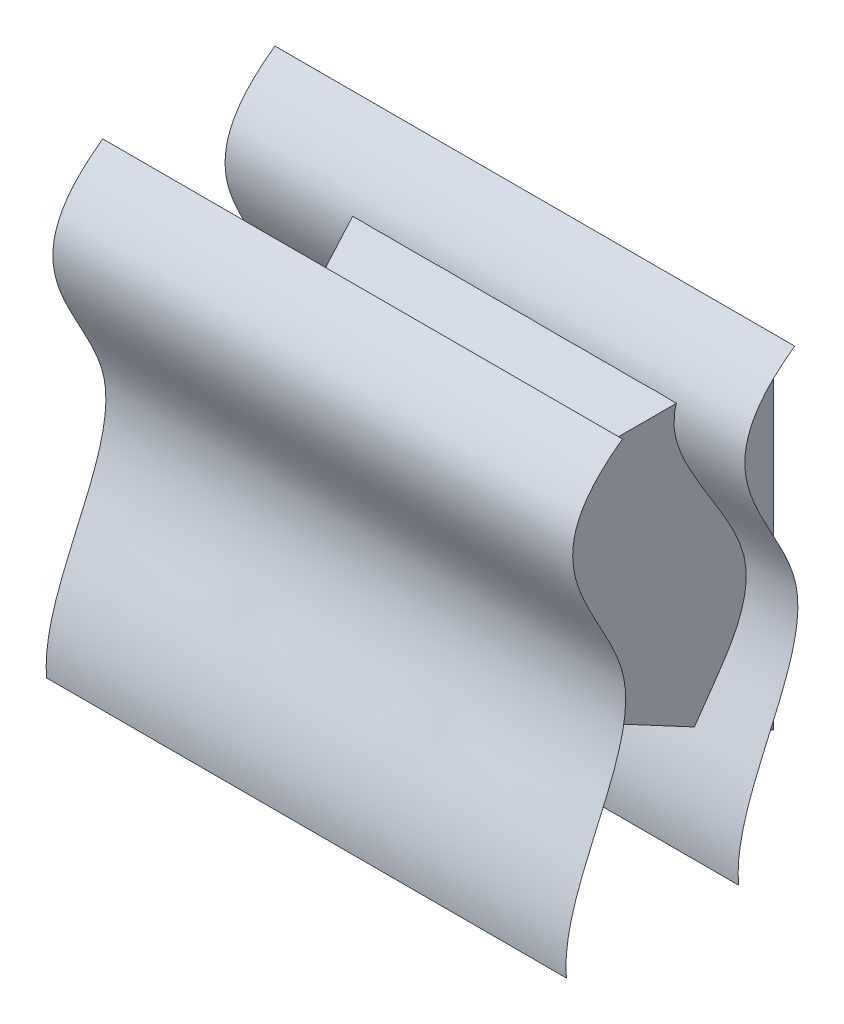
SolidWorks part; units mm, degrees
ref_plane "Спереди" through (0, 0, 0) normal (0, 0, 1) x (1, 0, 0)
ref_plane "Сверху" through (0, 0, 0) normal (0, 1, 0) x (1, 0, 0)
ref_plane "Справа" through (0, 0, 0) normal (1, 0, 0) x (0, 0, -1)
sketch "Эскиз1_fr" plane through (0, 0, 0) normal (0, 0, 1) x (1, 0, 0)
  line L1 (0, 0) -> (43.3507, 0)
  line L2 (0, 0) -> (0, -38.2597)
  line L3 (0, -38.2597) -> (43.3507, -38.2597)
  line L4 (43.3507, 0) -> (43.3507, -38.2597)
extrude "Бобышка-Вытянуть1" add sketch "Эскиз1_fr" along normal blind 20 draft 20
sketch "Эскиз1_rt" plane through (0, 0, 0) normal (1, 0, 0) x (0, 0, -1)
  spline S0 degree 3 poles (-24.0617, 6.19) (-36.3175, -2.5174) (-13.7833, -17.8971) (-31.3159, -35.3189) (-30.545, -44.4497) knots 0 0 0 0 0.484609 1 1 1 1
  point P2 (0, 0)
surface "Поверхность-Вытянуть2" sketch "Эскиз1_rt" parameters "D1"=50, "D2"=10
move or copy body "Тело-Переместить/Копировать1" bodies to move or copy 105 copy yes number of copies 1 translate (-1.5242, -2.1768, -21.3994)
